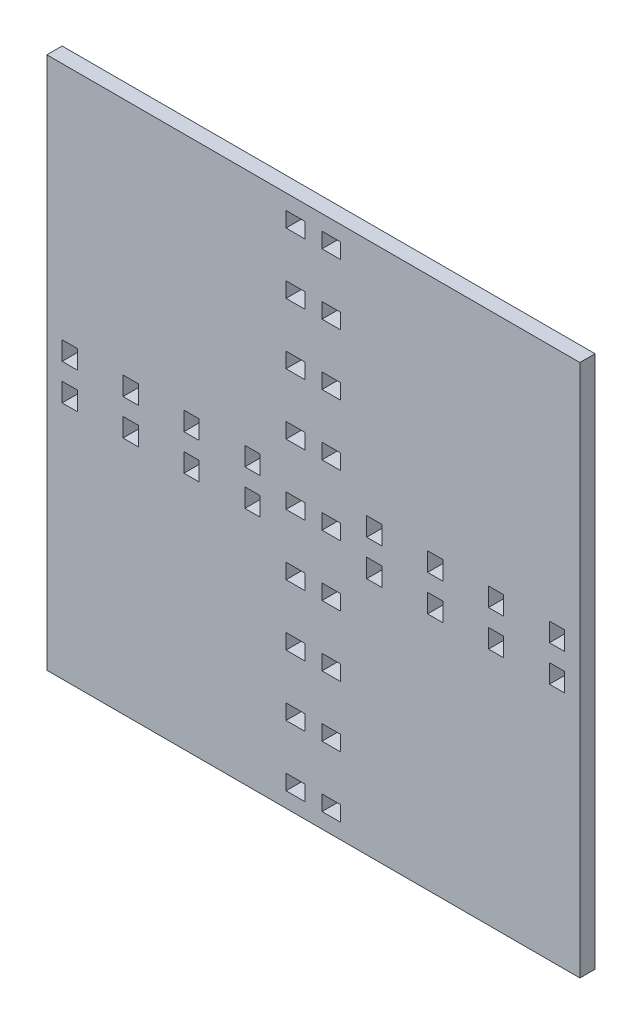
SolidWorks part; units mm, degrees
ref_plane "Front Plane" through (0, 0, 0) normal (0, 0, 1) x (1, 0, 0)
ref_plane "Top Plane" through (0, 0, 0) normal (0, 1, 0) x (1, 0, 0)
ref_plane "Right Plane" through (0, 0, 0) normal (1, 0, 0) x (0, 0, -1)
sketch "Sketch1" plane through (0, 0, 0) normal (0, 0, 1) x (1, 0, 0)
  line L1165 (21, 242.8) -> (21, 239.1172)
  line L1166 (21, 239.1172) -> (18, 239.1172)
  line L1167 (18, 239.1172) -> (18, 242.8)
  line L1168 (18, 242.8) -> (21, 242.8)
  line L1169 (9, 242.8) -> (9, 239.1172)
  line L1170 (9, 239.1172) -> (6, 239.1172)
  line L1171 (6, 239.1172) -> (6, 242.8)
  line L1172 (6, 242.8) -> (9, 242.8)
  line L1173 (33, 242.8) -> (33, 239.1172)
  line L1174 (33, 239.1172) -> (30, 239.1172)
  line L1175 (30, 239.1172) -> (30, 242.8)
  line L1176 (30, 242.8) -> (33, 242.8)
  line L1177 (53.8, 231) -> (50.1172, 231)
  line L1178 (50.1172, 231) -> (50.1172, 234)
  line L1179 (50.1172, 234) -> (53.8, 234)
  line L1180 (53.8, 234) -> (53.8, 231)
  line L1181 (53.8, 219) -> (50.1172, 219)
  line L1182 (50.1172, 219) -> (50.1172, 222)
  line L1183 (50.1172, 222) -> (53.8, 222)
  line L1184 (53.8, 222) -> (53.8, 219)
  line L1185 (53.8, 279) -> (50.1172, 279)
  line L1186 (50.1172, 279) -> (50.1172, 282)
  line L1187 (50.1172, 282) -> (53.8, 282)
  line L1188 (53.8, 282) -> (53.8, 279)
  line L1189 (53.8, 267) -> (50.1172, 267)
  line L1190 (50.1172, 267) -> (50.1172, 270)
  line L1191 (50.1172, 270) -> (53.8, 270)
  line L1192 (53.8, 270) -> (53.8, 267)
  line L1193 (81, 242.8) -> (81, 239.1172)
  line L1194 (81, 239.1172) -> (78, 239.1172)
  line L1195 (78, 239.1172) -> (78, 242.8)
  line L1196 (78, 242.8) -> (81, 242.8)
  line L1197 (93, 242.8) -> (93, 239.1172)
  line L1198 (93, 239.1172) -> (90, 239.1172)
  line L1199 (90, 239.1172) -> (90, 242.8)
  line L1200 (90, 242.8) -> (93, 242.8)
  line L1201 (53.8, 291) -> (50.1172, 291)
  line L1202 (50.1172, 291) -> (50.1172, 294)
  line L1203 (50.1172, 294) -> (53.8, 294)
  line L1204 (53.8, 294) -> (53.8, 291)
  line L1205 (9, 246.2) -> (6, 246.2)
  line L1206 (6, 246.2) -> (6, 249.8828)
  line L1207 (6, 249.8828) -> (9, 249.8828)
  line L1208 (9, 249.8828) -> (9, 246.2)
  line L1209 (21, 246.2) -> (18, 246.2)
  line L1210 (18, 246.2) -> (18, 249.8828)
  line L1211 (18, 249.8828) -> (21, 249.8828)
  line L1212 (21, 249.8828) -> (21, 246.2)
  line L1213 (33, 246.2) -> (30, 246.2)
  line L1214 (30, 246.2) -> (30, 249.8828)
  line L1215 (30, 249.8828) -> (33, 249.8828)
  line L1216 (33, 249.8828) -> (33, 246.2)
  line L1217 (69, 246.2) -> (66, 246.2)
  line L1218 (66, 246.2) -> (66, 249.8828)
  line L1219 (66, 249.8828) -> (69, 249.8828)
  line L1220 (69, 249.8828) -> (69, 246.2)
  line L1221 (45, 246.2) -> (42, 246.2)
  line L1222 (42, 246.2) -> (42, 249.8828)
  line L1223 (42, 249.8828) -> (45, 249.8828)
  line L1224 (45, 249.8828) -> (45, 246.2)
  line L1225 (81, 246.2) -> (78, 246.2)
  line L1226 (78, 246.2) -> (78, 249.8828)
  line L1227 (78, 249.8828) -> (81, 249.8828)
  line L1228 (81, 249.8828) -> (81, 246.2)
  line L1229 (93, 246.2) -> (90, 246.2)
  line L1230 (90, 246.2) -> (90, 249.8828)
  line L1231 (90, 249.8828) -> (93, 249.8828)
  line L1232 (93, 249.8828) -> (93, 246.2)
  line L1233 (105, 246.2) -> (102, 246.2)
  line L1234 (102, 246.2) -> (102, 249.8828)
  line L1235 (102, 249.8828) -> (105, 249.8828)
  line L1236 (105, 249.8828) -> (105, 246.2)
  line L1237 (42, 242.8) -> (45, 242.8)
  line L1238 (45, 242.8) -> (45, 239.1172)
  line L1239 (45, 239.1172) -> (42, 239.1172)
  line L1240 (42, 239.1172) -> (42, 242.8)
  line L1241 (66, 242.8) -> (69, 242.8)
  line L1242 (69, 242.8) -> (69, 239.1172)
  line L1243 (69, 239.1172) -> (66, 239.1172)
  line L1244 (66, 239.1172) -> (66, 242.8)
  line L1245 (102, 242.8) -> (105, 242.8)
  line L1246 (105, 242.8) -> (105, 239.1172)
  line L1247 (105, 239.1172) -> (102, 239.1172)
  line L1248 (102, 239.1172) -> (102, 242.8)
  line L1249 (57.2, 291) -> (57.2, 294)
  line L1250 (57.2, 294) -> (60.8828, 294)
  line L1251 (60.8828, 294) -> (60.8828, 291)
  line L1252 (60.8828, 291) -> (57.2, 291)
  line L1253 (57.2, 279) -> (57.2, 282)
  line L1254 (57.2, 282) -> (60.8828, 282)
  line L1255 (60.8828, 282) -> (60.8828, 279)
  line L1256 (60.8828, 279) -> (57.2, 279)
  line L1257 (57.2, 267) -> (57.2, 270)
  line L1258 (57.2, 270) -> (60.8828, 270)
  line L1259 (60.8828, 270) -> (60.8828, 267)
  line L1260 (60.8828, 267) -> (57.2, 267)
  line L1261 (57.2, 255) -> (57.2, 258)
  line L1262 (57.2, 258) -> (60.8828, 258)
  line L1263 (60.8828, 258) -> (60.8828, 255)
  line L1264 (60.8828, 255) -> (57.2, 255)
  line L1265 (57.2, 243) -> (57.2, 246)
  line L1266 (57.2, 246) -> (60.8828, 246)
  line L1267 (60.8828, 246) -> (60.8828, 243)
  line L1268 (60.8828, 243) -> (57.2, 243)
  line L1269 (57.2, 231) -> (57.2, 234)
  line L1270 (57.2, 234) -> (60.8828, 234)
  line L1271 (60.8828, 234) -> (60.8828, 231)
  line L1272 (60.8828, 231) -> (57.2, 231)
  line L1273 (57.2, 219) -> (57.2, 222)
  line L1274 (57.2, 222) -> (60.8828, 222)
  line L1275 (60.8828, 222) -> (60.8828, 219)
  line L1276 (60.8828, 219) -> (57.2, 219)
  line L1277 (57.2, 207) -> (57.2, 210)
  line L1278 (57.2, 210) -> (60.8828, 210)
  line L1279 (60.8828, 210) -> (60.8828, 207)
  line L1280 (60.8828, 207) -> (57.2, 207)
  line L1281 (57.2, 195) -> (57.2, 198)
  line L1282 (57.2, 198) -> (60.8828, 198)
  line L1283 (60.8828, 198) -> (60.8828, 195)
  line L1284 (60.8828, 195) -> (57.2, 195)
  line L1285 (53.8, 246) -> (53.8, 243)
  line L1286 (53.8, 243) -> (50.1172, 243)
  line L1287 (50.1172, 243) -> (50.1172, 246)
  line L1288 (50.1172, 246) -> (53.8, 246)
  line L1289 (53.8, 258) -> (53.8, 255)
  line L1290 (53.8, 255) -> (50.1172, 255)
  line L1291 (50.1172, 255) -> (50.1172, 258)
  line L1292 (50.1172, 258) -> (53.8, 258)
  line L1293 (53.8, 198) -> (53.8, 195)
  line L1294 (53.8, 195) -> (50.1172, 195)
  line L1295 (50.1172, 195) -> (50.1172, 198)
  line L1296 (50.1172, 198) -> (53.8, 198)
  line L1297 (53.8, 210) -> (53.8, 207)
  line L1298 (53.8, 207) -> (50.1172, 207)
  line L1299 (50.1172, 207) -> (50.1172, 210)
  line L1300 (50.1172, 210) -> (53.8, 210)
  line L1301 (3, 297) -> (108, 297)
  line L1302 (108, 297) -> (108, 192)
  line L1303 (108, 192) -> (3, 192)
  line L1304 (3, 192) -> (3, 297)
extrude "Boss-Extrude1" add sketch "Sketch1" along normal blind 3
